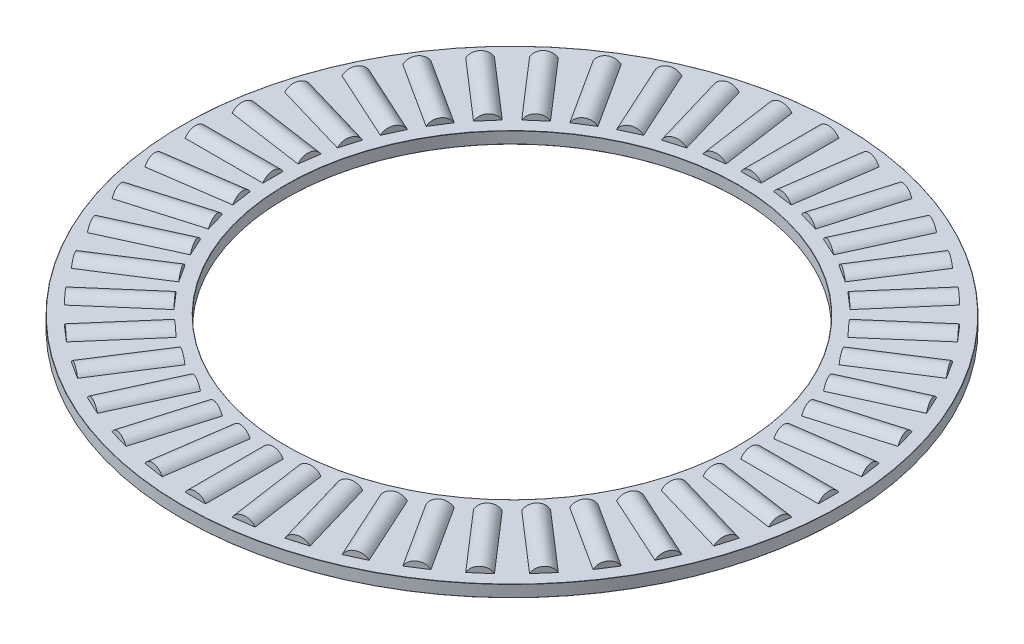
SolidWorks part; units mm, degrees
ref_plane "Front Plane" through (0, 0, 0) normal (0, 0, 1) x (1, 0, 0)
ref_plane "Top Plane" through (0, 0, 0) normal (0, 1, 0) x (1, 0, 0)
ref_plane "Right Plane" through (0, 0, 0) normal (1, 0, 0) x (0, 0, -1)
sketch "Sketch1" plane through (0, 0, 0) normal (1, 0, 0) x (0, 0, -1)
  line L0 (-27.7812, 0) -> (27.7812, 0) construction
  line L1 (0, -0.9922) -> (0, 0.9922) construction
  line L2 (-27.7812, 0.4961) -> (-19.05, 0.4961)
  line L3 (-27.7812, 0.4961) -> (-27.7812, -0.4961)
  line L4 (-27.7812, -0.4961) -> (-19.05, -0.4961)
  line L5 (-19.05, 0.4961) -> (-19.05, -0.4961)
  line L7 (-23.4156, 0.9922) -> (-23.4156, 0.4961) construction
  line L8 (-26.6898, 0.9922) -> (-20.1414, 0.9922) construction
  line L9 (-26.6898, 0.9922) -> (-26.6898, -0.9922) construction
  line L10 (-26.6898, -0.9922) -> (-20.1414, -0.9922) construction
  line L11 (-20.1414, 0.9922) -> (-20.1414, -0.9922) construction
  point P16 (-26.6898, 0)
  dimension "OD" = 55.5625
  dimension "Shaft Dia" = 38.1
  dimension "Th" = 1.9844
  dimension "D2" = 0.9922
  dimension "D1" = 6.5484
  dimension "D3" = 8.7312
revolve "Revolve1" add sketch "Sketch1" angle 360 about L1
sketch "Sketch3" plane through (0, 0, 0) normal (1, 0, 0) x (0, 0, -1)
  line L0 (-26.6898, 0.9922) -> (-26.6898, -0.9922) construction
  line L1 (-26.6898, 0) -> (-20.1414, 0)
  line L2 (-26.6898, 0) -> (-26.6898, 0.9922)
  line L3 (-26.6898, 0.9922) -> (-20.1414, 0.9922)
  line L4 (-20.1414, 0) -> (-20.1414, 0.9922)
revolve "Cut-Revolve1" cut sketch "Sketch3" angle 360 about L1
sketch "Sketch2" plane through (0, 0, 0) normal (1, 0, 0) x (0, 0, -1)
  line L1 (-26.6898, 0) -> (-20.1414, 0)
  line L2 (-26.6898, 0) -> (-26.6898, 0.9922)
  line L3 (-26.6898, 0.9922) -> (-20.1414, 0.9922)
  line L4 (-20.1414, 0) -> (-20.1414, 0.9922)
revolve "Revolve2" add sketch "Sketch2" angle 360 about L1
ref_axis "Axis1" through (0, 0.9922, 0) along (0, -1, 0)
pattern_circular "CirPattern1" count 44 every 8.182 about axis through (0, 0.9922, 0) along (0, -1, 0) of bodies 187 411
pattern_circular "CirPattern2" count 44 every 8.182 about axis through (0, 0, 0) along (0, 1, 0) of "Cut-Revolve1"
sketch "Sketch4" plane through (0, 0, 0) normal (1, 0, 0) x (0, 0, -1)
  line L0 (-27.7812, 0.4961) -> (-27.7812, -0.4961) construction
  line L1 (-27.7812, 9.1091) -> (-19.05, 9.1091)
  line L2 (-27.7812, 9.1091) -> (-27.7813, 9.9219)
  line L3 (-27.7813, 9.9219) -> (-19.05, 9.9219)
  line L4 (-19.05, 9.1091) -> (-19.05, 9.9219)
  line L5 (-27.7812, -9.9219) -> (-19.05, -9.9219)
  line L6 (-27.7812, -9.9219) -> (-27.7812, -9.1091)
  line L7 (-27.7812, -9.1091) -> (-19.05, -9.1091)
  line L8 (-19.05, -9.9219) -> (-19.05, -9.1091)
  line L10 (-19.05, 0.4961) -> (-19.05, -0.4961) construction
  line L11 (0, 0) -> (-27.7812, 0) construction
  line L12 (-27.7812, 0) -> (27.7812, 0) construction
  line L13 (0, -0.9922) -> (0, 0.9922) construction
  dimension "Ht" = 19.8438
  dimension "Washer Th" = 0.8128
  dimension "Washer ID" = 38.1
  dimension "Washer OD" = 55.5625
revolve "Revolve3" [suppressed] add sketch "Sketch4" angle 360 about L1
fillet "Fillet1" [suppressed] radius 0.0198
fillet "Fillet2" radius 0.0198 4 edges at (0, -0.4961, -19.05) (0, 0.4961, -19.05) (0, -0.4961, -27.7812) (0, 0.4961, -27.7812)
fillet "Fillet3" [suppressed] radius 0.0198
equation "\"D2@Sketch1\" = \"Th@Sketch1\"*.5"
equation "\"D1@Fillet1\" = \"Th@Sketch1\"*.01"
equation "\"D1@Fillet2\" = \"D1@Fillet1\""
equation "\"D1@Fillet3\" = \"D1@Fillet1\""
equation "\"D1@Sketch1\" = \"D3@Sketch1\"*.75"
equation "\"Angle@CirPattern1\" = 360/\"Rollers@CirPattern1\""
equation "\"Rollers@CirPattern1\" = \"OD@Sketch1\"*20"
equation "\"D1@CirPattern2\" = \"Rollers@CirPattern1\""
equation "\"D2@CirPattern2\" = \"Angle@CirPattern1\""
equation "\"Ht@Sketch4\" = \"Th@Sketch1\"*10"
